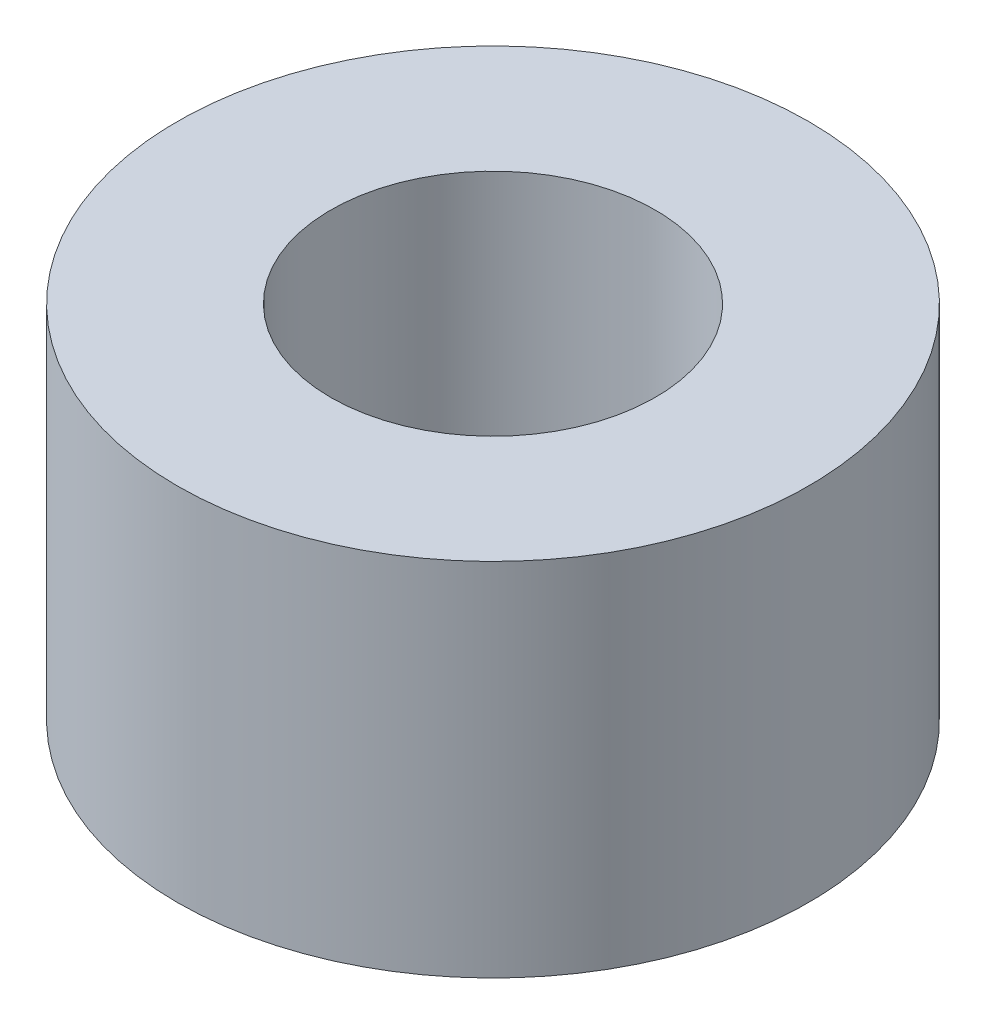
SolidWorks part; units mm, degrees
ref_plane "Płaszczyzna przednia" through (0, 0, 0) normal (0, 0, 1) x (1, 0, 0)
ref_plane "Płaszczyzna górna" through (0, 0, 0) normal (0, 1, 0) x (1, 0, 0)
ref_plane "Płaszczyzna prawa" through (0, 0, 0) normal (1, 0, 0) x (0, 0, -1)
sketch "Sketch1" plane through (0, 0, 0) normal (0, 1, 0) x (1, 0, 0)
  circle A0 centre (0, 0) radius 1.8
  circle A1 centre (0, 0) radius 3.5
extrude "Boss-Extrude1" add sketch "Sketch1" along normal blind 4
